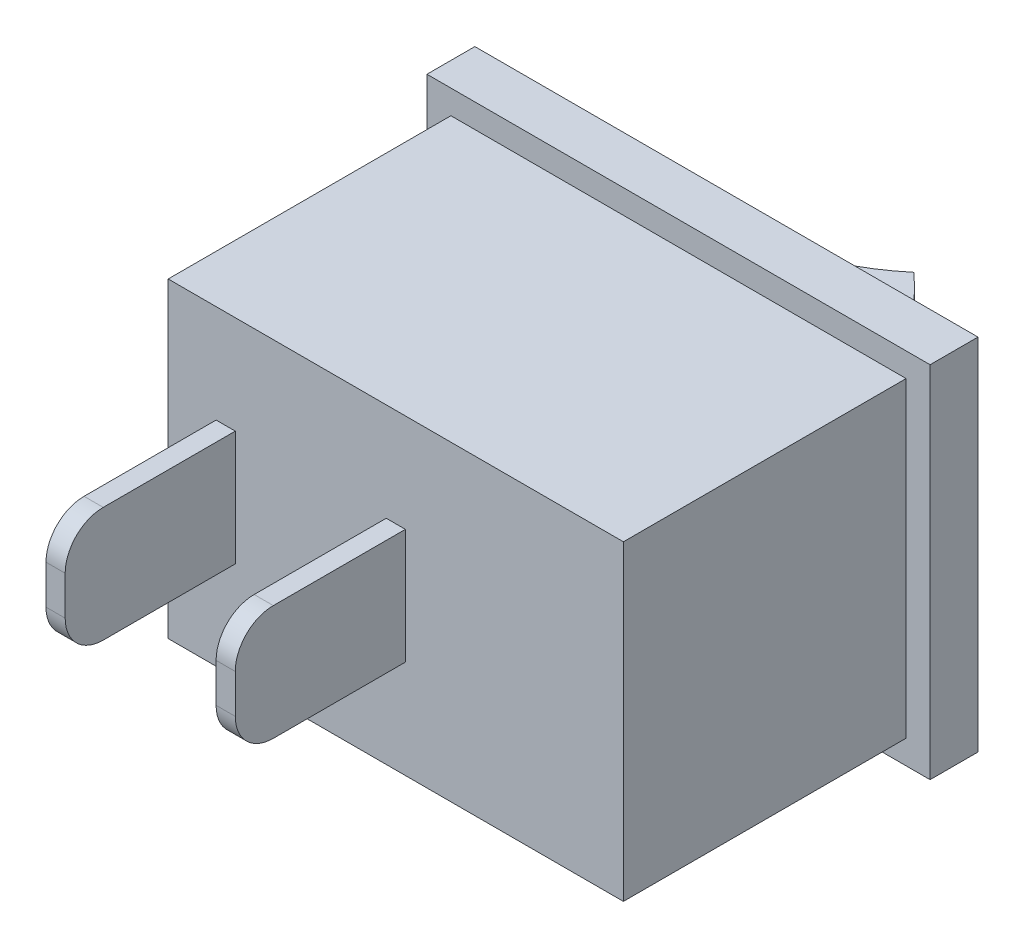
SolidWorks part; units mm, degrees
ref_plane "Front Plane" through (0, 0, 0) normal (0, 0, 1) x (1, 0, 0)
ref_plane "Top Plane" through (0, 0, 0) normal (0, 1, 0) x (1, 0, 0)
ref_plane "Right Plane" through (0, 0, 0) normal (1, 0, 0) x (0, 0, -1)
sketch "Sketch1" plane through (0, 0, 0) normal (0, 0, 1) x (1, 0, 0)
  line L1 (0, 0) -> (21, 0)
  line L2 (0, 0) -> (0, 15)
  line L3 (0, 15) -> (21, 15)
  line L4 (21, 0) -> (21, 15)
  dimension "D1" = 15
  dimension "D2" = 21
extrude "Boss-Extrude1" add sketch "Sketch1" along normal blind 2
ref_plane "Plane1" through (0, 7.5, 0) normal (0, -1, 0) x (-1, 0, 0)
sketch "Sketch2" plane through (0, 7.5, 0) normal (0, -1, 0) x (-1, 0, 0)
  line L0 (-14.818, 3.5) -> (-14.818, 0) construction
  line L1 (0, 0) -> (-21, 0) construction
  line L2 (0, -2) -> (-21, -2) construction
  line L3 (-10.5, 0) -> (-10.5, -2) construction
  line L4 (-14.818, 0) -> (-17.358, 0)
  line L5 (-14.818, 0) -> (-3.642, 0)
  spline S0 degree 2 poles (-17.358, 0) (-16.7077, 1.8396) (-14.818, 3.5) knots 0 0 0 1 1 1
  spline S1 degree 3 poles (-14.818, 3.5) (-12.3128, 1.3711) (-7.9646, 0.3921) (-3.642, 0) knots 0 0 0 0 1 1 1 1
  dimension "D1" = 5.5
  dimension "D2" = 2.54
  dimension "D3" = 4.318
  dimension "D4" = 6.858
extrude "Boss-Extrude2" add sketch "Sketch2" along normal mid plane 10
sketch "Sketch3" plane through (0, 0, 2) normal (0, 0, 1) x (1, 0, 0)
  line L0 (10.5, 14) -> (10.5, 15) construction
  line L1 (1, 14) -> (20, 14)
  line L2 (1, 14) -> (1, 1)
  line L3 (1, 1) -> (20, 1)
  line L4 (20, 14) -> (20, 1)
  line L5 (21, 15) -> (0, 15) construction
  line L6 (1, 7.5) -> (0, 7.5) construction
  line L7 (0, 15) -> (0, 0) construction
  dimension "D1" = 19
  dimension "D2" = 13
extrude "Boss-Extrude3" add sketch "Sketch3" along normal blind 11.8
sketch "Sketch4" plane through (0, 0, 13.8) normal (0, 0, 1) x (1, 0, 0)
  line L0 (3, 7.5) -> (0, 7.5) construction
  line L1 (3, 9.9) -> (3.8, 9.9)
  line L2 (3, 9.9) -> (3, 5.1)
  line L3 (3, 5.1) -> (3.8, 5.1)
  line L4 (3.8, 9.9) -> (3.8, 5.1)
  line L5 (10.1, 9.9) -> (10.9, 9.9)
  line L6 (10.1, 9.9) -> (10.1, 5.1)
  line L7 (10.1, 5.1) -> (10.9, 5.1)
  line L8 (10.9, 9.9) -> (10.9, 5.1)
  line L9 (0, 15) -> (0, 0) construction
  line L10 (3.8, 7.5) -> (10.1, 7.5) construction
  line L11 (10.5, 9.9) -> (10.5, 15) construction
  line L12 (21, 15) -> (0, 15) construction
  dimension "D1" = 0.8
  dimension "D2" = 0.8
  dimension "D3" = 4.8
  dimension "D4" = 4.8
  dimension "D5" = 7.1
extrude "Boss-Extrude4" add sketch "Sketch4" along normal blind 7.1
fillet "Fillet1" radius 1.5875 4 edges at (10.5, 9.9, 20.9) (10.5, 5.1, 20.9) (3.4, 5.1, 20.9) (3.4, 9.9, 20.9)
equation "\"D4@Sketch2\"=\"D2@Sketch2\"+\"D3@Sketch2\""
